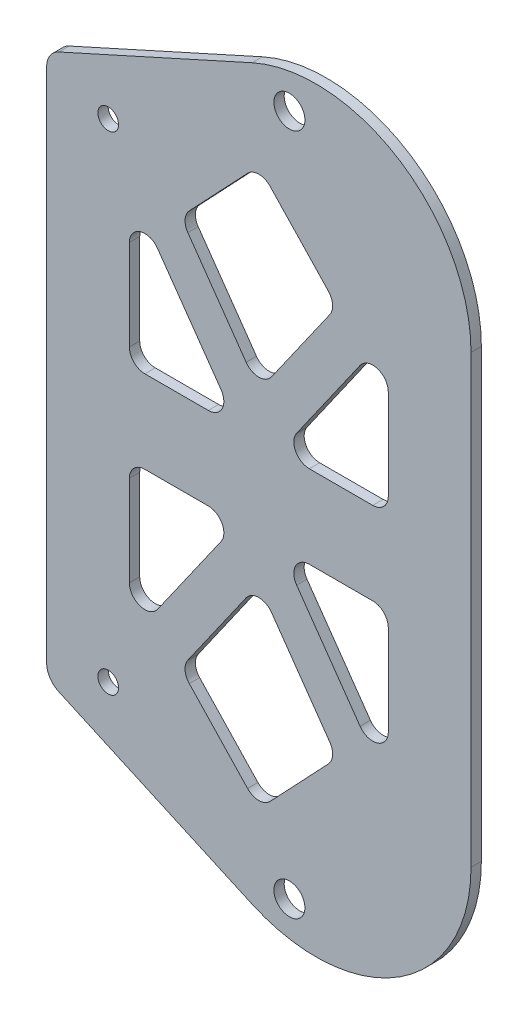
SolidWorks part; units mm, degrees
ref_plane "Alzado" through (0, 0, 0) normal (0, 0, 1) x (1, 0, 0)
ref_plane "Planta" through (0, 0, 0) normal (0, 1, 0) x (1, 0, 0)
ref_plane "Vista lateral" through (0, 0, 0) normal (1, 0, 0) x (0, 0, -1)
sketch "Croquis1" plane through (0, 0, 0) normal (0, 0, 1) x (1, 0, 0)
  line L0 (-15.9432, 28.5305) -> (-11.9432, 28.5305) construction
  line L1 (-11.9432, 28.5305) -> (-11.9432, 73.3287) construction
  line L2 (-11.9432, 73.3287) -> (-11.9432, -16.2677)
  line L3 (-52.8033, 52.6761) -> (-51.3858, 49.5382)
  line L4 (-51.3858, 7.5227) -> (-52.8033, 4.3848)
  line L5 (-51.804, 55.3221) -> (-11.9432, 73.3287)
  line L6 (-51.804, 1.7388) -> (-11.9432, -16.2677)
  arc A0 (-48.6554, 48.5794) -> (-48.6554, 8.4815) centre (-38.4432, 28.5305) cw
  circle A1 centre (-29.5067, 61.5151) radius 1.5
  circle A2 centre (-47.0279, 52.1168) radius 1
  circle A3 centre (-47.0279, 4.9442) radius 1
  circle A4 centre (-29.5067, -4.4541) radius 1.5
  arc A5 (-51.804, 55.3221) -> (-52.8033, 52.6761) centre (-50.9807, 53.4995) ccw
  arc A6 (-51.3858, 49.5382) -> (-48.6554, 48.5794) centre (-49.5632, 50.3616) ccw
  arc A7 (-48.6554, 8.4815) -> (-51.3858, 7.5227) centre (-49.5632, 6.6994) ccw
  arc A8 (-52.8033, 4.3848) -> (-51.804, 1.7388) centre (-50.9807, 3.5615) ccw
  dimension "D1" = 4
sketch "Croquis3" plane through (0, 0, 0) normal (0, 0, 1) x (1, 0, 0)
  line L0 (-52.9807, 53.4995) -> (-52.9807, 3.5615)
  line L1 (-51.804, 55.3221) -> (-11.9432, 73.3287)
  line L2 (-11.9432, 73.3287) -> (-11.9432, -16.2677)
  line L3 (-11.9432, 28.5305) -> (-52.9807, 28.5305) construction
  line L4 (-51.804, 1.7388) -> (-11.9432, -16.2677)
  circle A0 centre (-47.0279, 52.1168) radius 1
  circle A1 centre (-29.5067, 61.5151) radius 1.5
  circle A2 centre (-47.0279, 4.9442) radius 1
  circle A3 centre (-29.5067, -4.4541) radius 1.5
  arc A4 (-51.804, 55.3221) -> (-52.8033, 52.6761) centre (-50.9807, 53.4995) ccw construction
  arc A6 (-52.9807, 53.4995) -> (-51.804, 55.3221) centre (-50.9807, 53.4995) cw
  arc A7 (-52.9807, 3.5615) -> (-51.804, 1.7388) centre (-50.9807, 3.5615) ccw
  circle A8 centre (-29.5067, -4.4541) radius 1.5
  circle A9 centre (-47.0279, 4.9442) radius 1
extrude "Saliente-Extruir1" add sketch "Croquis3" along normal blind 1 contours L2 L3 L0 A7 L4 A3 A2 | L3 L2 L1 A6 L0 A0 A1
fillet "Redondeo1" radius 15 2 edges at (-11.9432, -16.2677, 0.5) (-11.9432, 73.3287, 0.5)
sketch "Croquis4" plane through (0, 0, 1) normal (0, 0, 1) x (1, 0, 0)
  line L0 (-52.9807, 28.5305) -> (-11.9432, 28.5305) construction
  line L1 (-52.9807, 53.4995) -> (-52.9807, 3.5615) construction
  line L2 (-11.9432, 50.0931) -> (-11.9432, 6.9678) construction
  line L3 (-44.9807, 34.0305) -> (-44.9807, 42.7789)
  line L4 (-42.2525, 43.6401) -> (-36.1178, 34.8917)
  line L5 (-37.3459, 32.5305) -> (-43.4807, 32.5305)
  line L6 (-32.462, 28.5305) -> (-32.462, 64.041) construction
  line L7 (-22.6714, 43.6401) -> (-28.8061, 34.8917)
  line L8 (-19.9432, 34.0305) -> (-19.9432, 42.7789)
  line L9 (-27.578, 32.5305) -> (-21.4432, 32.5305)
  line L10 (-33.552, 54.2875) -> (-39.188, 48.3253)
  line L11 (-39.326, 46.4336) -> (-33.6901, 38.3966)
  line L12 (-25.5979, 46.4336) -> (-31.2338, 38.3966)
  line L13 (-31.3719, 54.2875) -> (-25.7359, 48.3253)
  line L14 (-31.3719, 2.7735) -> (-25.7359, 8.7357)
  line L15 (-25.5979, 10.6273) -> (-31.2338, 18.6643)
  line L16 (-39.326, 10.6273) -> (-33.6901, 18.6643)
  line L17 (-33.552, 2.7735) -> (-39.188, 8.7357)
  line L18 (-27.578, 24.5305) -> (-21.4432, 24.5305)
  line L19 (-19.9432, 23.0305) -> (-19.9432, 14.2821)
  line L20 (-22.6714, 13.4209) -> (-28.8061, 22.1693)
  line L21 (-37.3459, 24.5305) -> (-43.4807, 24.5305)
  line L22 (-42.2525, 13.4209) -> (-36.1178, 22.1693)
  line L23 (-44.9807, 23.0305) -> (-44.9807, 14.2821)
  arc A0 (-11.9432, 50.0931) -> (-33.1184, 63.7631) centre (-26.9432, 50.0931) ccw construction
  arc A1 (-19.9432, 14.2821) -> (-22.6714, 13.4209) centre (-21.4432, 14.2821) cw
  arc A2 (-21.4432, 24.5305) -> (-19.9432, 23.0305) centre (-21.4432, 23.0305) cw
  arc A3 (-27.578, 24.5305) -> (-28.8061, 22.1693) centre (-27.578, 23.0305) ccw
  arc A4 (-25.7359, 8.7357) -> (-25.5979, 10.6273) centre (-26.826, 9.7661) ccw
  arc A5 (-31.3719, 2.7735) -> (-33.552, 2.7735) centre (-32.462, 3.8039) cw
  arc A6 (-39.326, 10.6273) -> (-39.188, 8.7357) centre (-38.0979, 9.7661) ccw
  arc A7 (-31.2338, 18.6643) -> (-33.6901, 18.6643) centre (-32.462, 17.8031) ccw
  arc A8 (-37.3459, 24.5305) -> (-36.1178, 22.1693) centre (-37.3459, 23.0305) cw
  arc A9 (-42.2525, 13.4209) -> (-44.9807, 14.2821) centre (-43.4807, 14.2821) cw
  arc A10 (-43.4807, 24.5305) -> (-44.9807, 23.0305) centre (-43.4807, 23.0305) ccw
  arc A11 (-19.9432, 34.0305) -> (-21.4432, 32.5305) centre (-21.4432, 34.0305) cw
  arc A12 (-28.8061, 34.8917) -> (-27.578, 32.5305) centre (-27.578, 34.0305) ccw
  arc A13 (-22.6714, 43.6401) -> (-19.9432, 42.7789) centre (-21.4432, 42.7789) cw
  arc A14 (-25.5979, 46.4336) -> (-25.7359, 48.3253) centre (-26.826, 47.2949) ccw
  arc A15 (-33.6901, 38.3966) -> (-31.2338, 38.3966) centre (-32.462, 39.2578) ccw
  arc A16 (-33.552, 54.2875) -> (-31.3719, 54.2875) centre (-32.462, 53.257) cw
  arc A17 (-39.188, 48.3253) -> (-39.326, 46.4336) centre (-38.0979, 47.2949) ccw
  arc A18 (-36.1178, 34.8917) -> (-37.3459, 32.5305) centre (-37.3459, 34.0305) cw
  arc A19 (-44.9807, 34.0305) -> (-43.4807, 32.5305) centre (-43.4807, 34.0305) ccw
  arc A20 (-44.9807, 42.7789) -> (-42.2525, 43.6401) centre (-43.4807, 42.7789) cw
  point P14 (-40.0288, 47.5305)
  point P34 (-19.9432, 9.5305)
  point P37 (-19.9432, 24.5305)
  point P40 (-30.462, 24.5305)
  point P43 (-24.8951, 9.6252)
  point P46 (-32.462, 1.6203)
  point P49 (-40.0288, 9.6252)
  point P52 (-32.462, 20.4157)
  point P55 (-34.462, 24.5305)
  point P58 (-44.9807, 9.5305)
  point P61 (-44.9807, 24.5305)
  point P64 (-19.9432, 32.5305)
  point P67 (-30.462, 32.5305)
  point P70 (-19.9432, 47.5305)
  point P73 (-24.8951, 47.4358)
  point P76 (-32.462, 36.6453)
  point P79 (-32.462, 55.4406)
  point P82 (-40.0288, 47.4358)
  point P85 (-34.462, 32.5305)
  point P88 (-44.9807, 32.5305)
  point P91 (-44.9807, 47.5305)
  dimension "D6" = 1.5
  dimension "D1" = 4
  dimension "D2" = 8
  dimension "D3" = 2
  dimension "D4" = 15
  dimension "D5" = 4
extrude "Cortar-Extruir1" cut sketch "Croquis4" against normal blind 1
